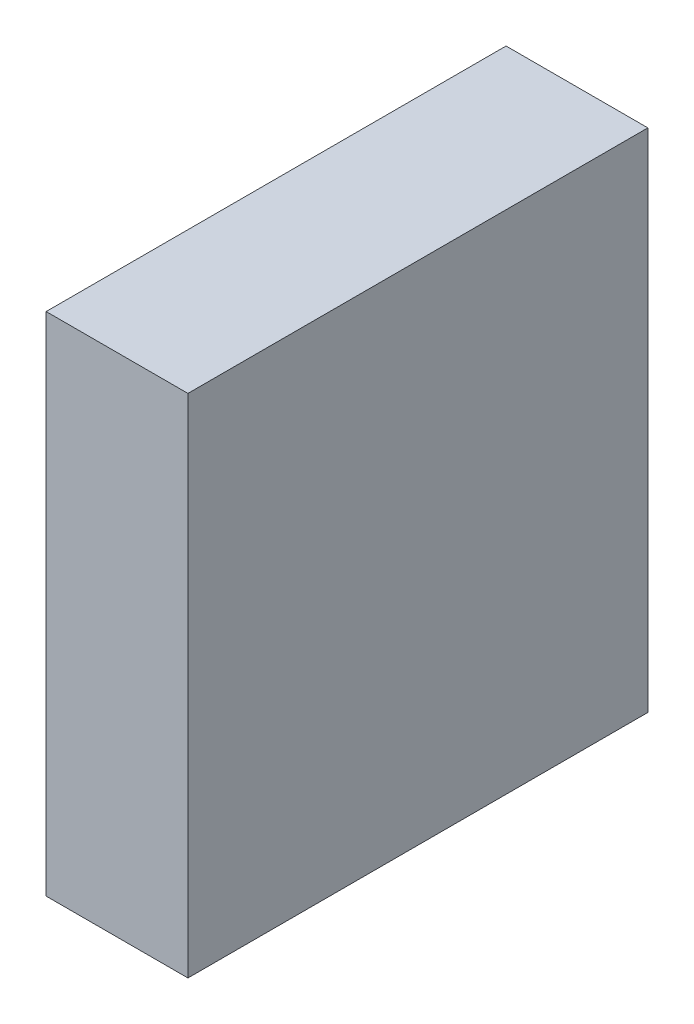
SolidWorks part; units mm, degrees
ref_plane "Front Plane" through (0, 0, 0) normal (0, 0, 1) x (1, 0, 0)
ref_plane "Top Plane" through (0, 0, 0) normal (0, 1, 0) x (1, 0, 0)
ref_plane "Right Plane" through (0, 0, 0) normal (1, 0, 0) x (0, 0, -1)
sketch "Sketch2" plane through (0, 0, 0) normal (0, 1, 0) x (1, 0, 0)
  line L1 (0, 0) -> (19.812, 0)
  line L2 (0, 0) -> (0, 64.262)
  line L3 (0, 64.262) -> (19.812, 64.262)
  line L4 (19.812, 0) -> (19.812, 64.262)
  dimension "D1" = 19.812
  dimension "D2" = 64.262
extrude "Boss-Extrude1" add sketch "Sketch2" along normal blind 70.739
